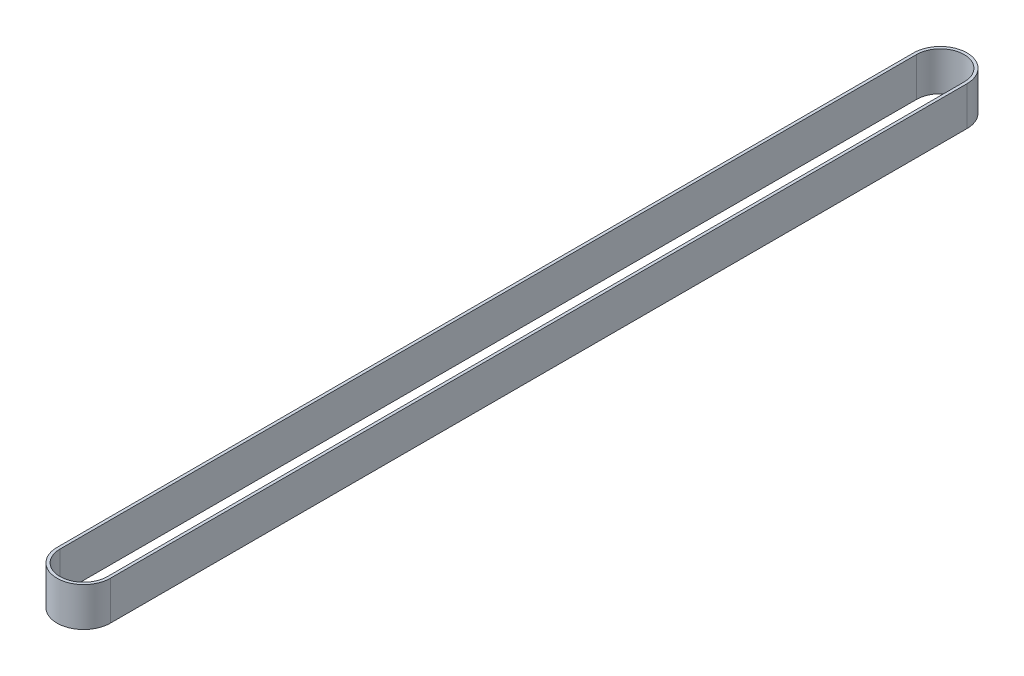
SolidWorks part; units mm, degrees
material "天然橡胶"
ref_plane "前视基准面" through (0, 0, 0) normal (0, 0, 1) x (1, 0, 0)
ref_plane "上视基准面" through (0, 0, 0) normal (0, 1, 0) x (1, 0, 0)
ref_plane "右视基准面" through (0, 0, 0) normal (1, 0, 0) x (0, 0, -1)
other "Configuration Table"
sketch "草图1" plane through (0, 0, 0) normal (0, 1, 0) x (1, 0, 0)
  line L0 (0, -110.05) -> (0, 110.05) construction
  line L1 (-6.86, -110.05) -> (-6.86, 110.05)
  line L2 (6.86, -110.05) -> (6.86, 110.05)
  line L3 (0, -110.05) -> (0, 110.05) construction
  line L4 (-6.11, -110.05) -> (-6.11, 110.05)
  line L5 (6.11, -110.05) -> (6.11, 110.05)
  arc A0 (-6.86, -110.05) -> (6.86, -110.05) centre (0, -110.05) ccw
  arc A1 (6.86, 110.05) -> (-6.86, 110.05) centre (0, 110.05) ccw
  arc A2 (-6.11, -110.05) -> (6.11, -110.05) centre (0, -110.05) ccw
  arc A3 (6.11, 110.05) -> (-6.11, 110.05) centre (0, 110.05) ccw
  point P2 (0, 0)
  point P9 (0, 0)
  dimension "D3" = 6.11
  dimension "D4" = 6.86
  dimension "D1" = 220.1
  dimension "D2" = 220.1
extrude "凸台-拉伸1" add sketch "草图1" along normal blind 10
